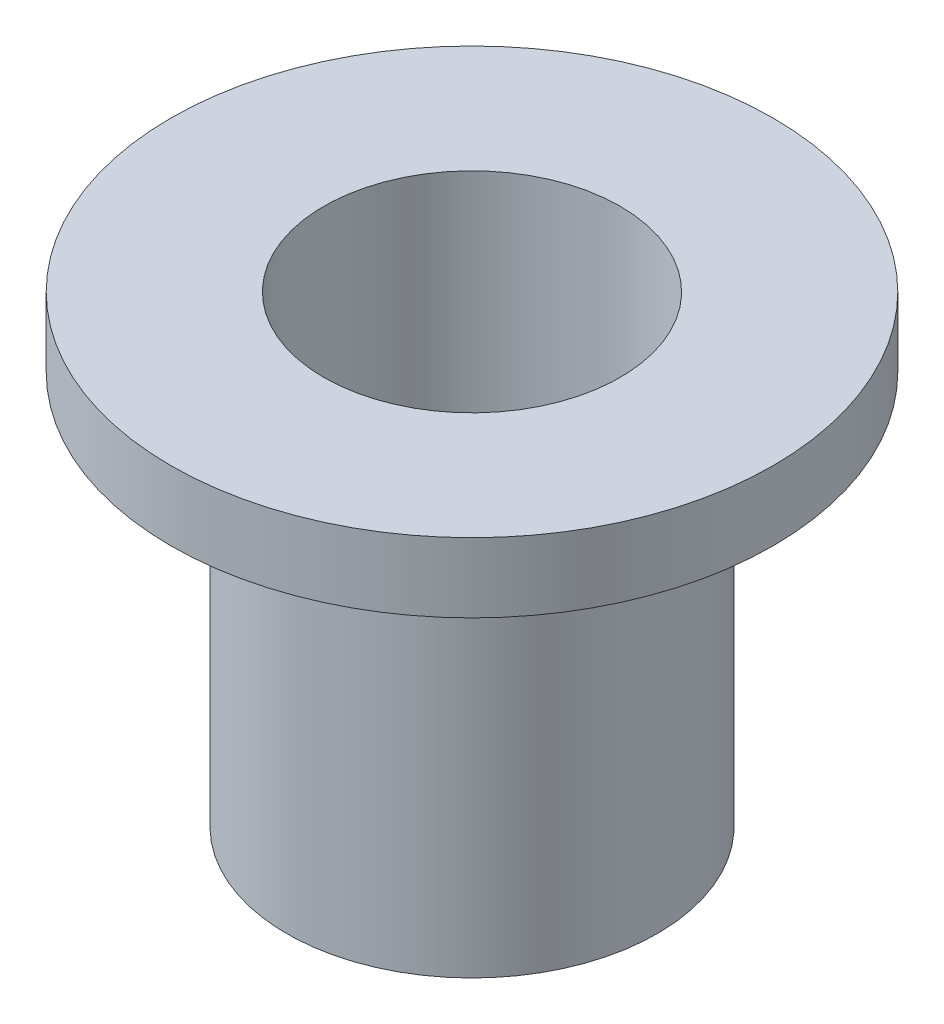
SolidWorks part; units mm, degrees
material "Простая углеродистая сталь"
ref_plane "Спереди" through (0, 0, 0) normal (0, 0, 1) x (1, 0, 0)
ref_plane "Сверху" through (0, 0, 0) normal (0, 1, 0) x (1, 0, 0)
ref_plane "Справа" through (0, 0, 0) normal (1, 0, 0) x (0, 0, -1)
sketch "Эскиз1" plane through (0, 0, 0) normal (1, 0, 0) x (0, 0, -1)
  line L0 (-3.2, 0) -> (-3.2, 10)
  line L1 (-3.2, 10) -> (-6.5, 10)
  line L2 (-6.5, 10) -> (-6.5, 8.5)
  line L3 (-6.5, 8.5) -> (-4, 8.5)
  line L4 (-4, 8.5) -> (-4, 0)
  line L5 (-3.2, 0) -> (-4, 0)
  line L6 (0, 0) -> (0.3771, 0.3804) construction
  line L7 (0, -11.9885) -> (0, 13.041) construction
  dimension "D1" = 3.2
  dimension "D2" = 4
  dimension "D3" = 1.5
  dimension "D4" = 10
  dimension "D5" = 6.5
revolve "Повернуть1" add sketch "Эскиз1" angle 360 about L7
